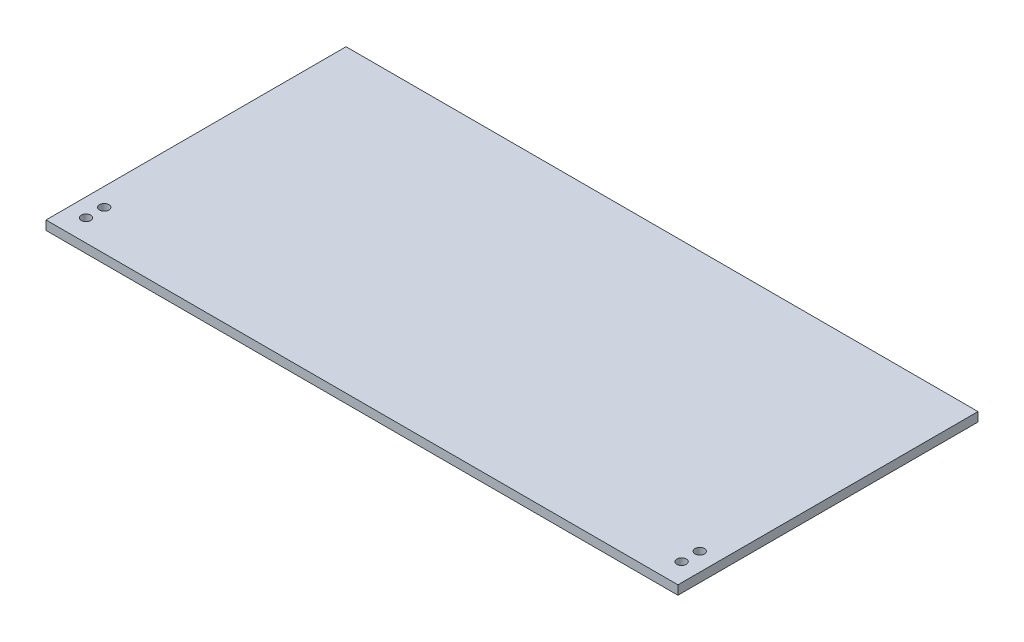
SolidWorks part; units mm, degrees
ref_plane "前视基准面" through (0, 0, 0) normal (0, 0, 1) x (1, 0, 0)
ref_plane "上视基准面" through (0, 0, 0) normal (0, 1, 0) x (1, 0, 0)
ref_plane "右视基准面" through (0, 0, 0) normal (1, 0, 0) x (0, 0, -1)
other "Configuration Table"
ref_plane "基准面1" through (0, 5, 0) normal (0, 1, 0) x (1, 0, 0)
sketch "草图1" plane through (0, 5, 0) normal (0, 1, 0) x (1, 0, 0)
  line L0 (173.75, -82.5) -> (173.75, 82.5)
  line L1 (173.75, 82.5) -> (-173.75, 82.5)
  line L2 (-173.75, 82.5) -> (-173.75, -82.5)
  line L3 (-173.75, -82.5) -> (173.75, -82.5)
  circle A0 centre (-163.75, -70.5) radius 2.6
  circle A1 centre (-163.75, -60.5) radius 2.6
  circle A2 centre (163.75, -60.5) radius 2.6
  circle A3 centre (163.75, -70.5) radius 2.6
extrude "凸台-拉伸1" add sketch "草图1" against normal blind 5
sketch "草图2" plane through (0, 5, 0) normal (0, 1, 0) x (1, 0, 0)
  line L0 (173.75, -55.3346) -> (-173.75, -55.3346)
  line L1 (0, 82.5) -> (0, -82.5) construction
  line L2 (-17.2038, 82.5) -> (-17.2038, -82.5)
  line L4 (-173.75, -82.5) -> (173.75, -82.5)
  line L5 (173.75, -82.5) -> (173.75, 82.5)
  line L6 (173.75, 82.5) -> (-173.75, 82.5)
  line L7 (-173.75, 82.5) -> (-173.75, -82.5)
  line L8 (-173.75, -82.5) -> (173.75, -82.5)
  line L9 (173.75, -82.5) -> (173.75, 82.5)
  line L10 (173.75, 82.5) -> (-173.75, 82.5)
  line L11 (-173.75, 82.5) -> (-173.75, -82.5)
  dimension "D1" = 0
